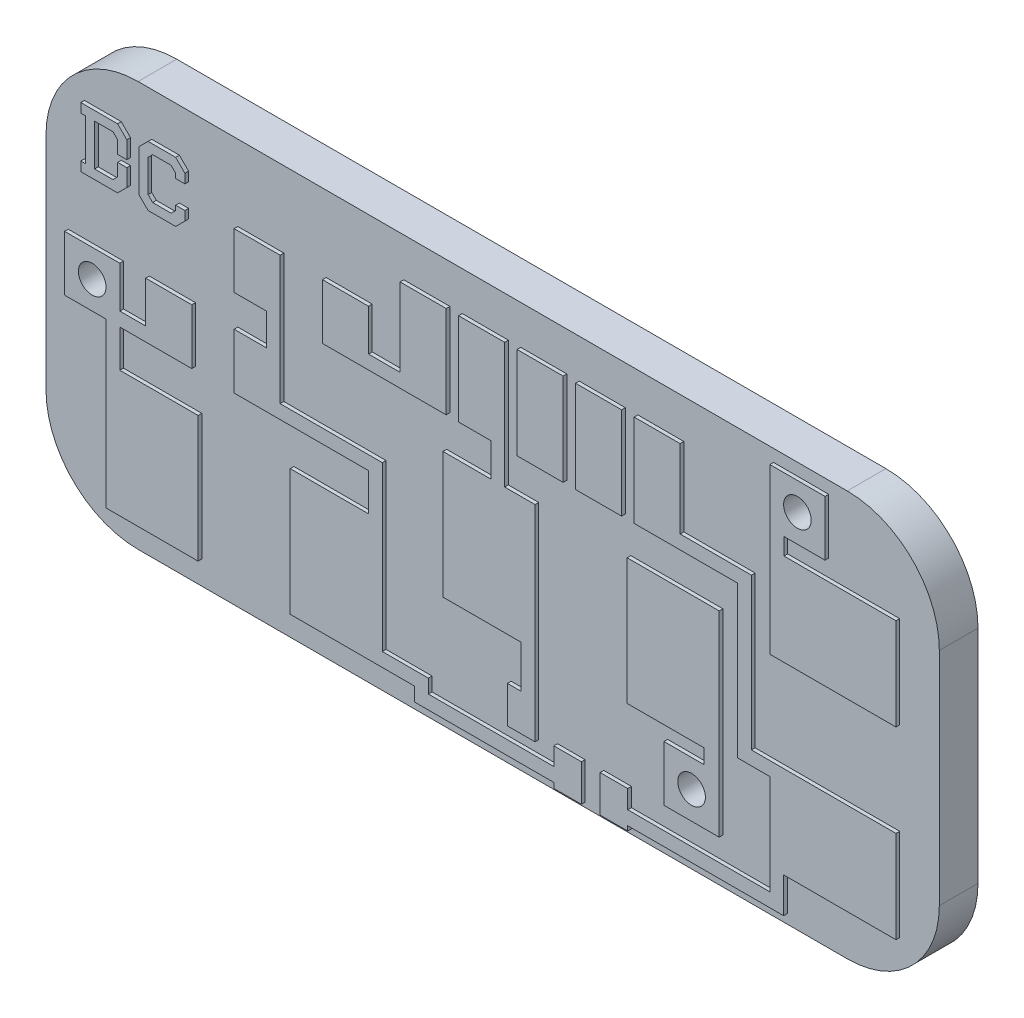
SolidWorks part; units mm, degrees
ref_plane "Front Plane" through (0, 0, 0) normal (0, 0, 1) x (1, 0, 0)
ref_plane "Top Plane" through (0, 0, 0) normal (0, 1, 0) x (1, 0, 0)
ref_plane "Right Plane" through (0, 0, 0) normal (1, 0, 0) x (0, 0, -1)
sketch "Sketch1" plane through (0, 0, 0) normal (0, 0, 1) x (1, 0, 0)
  line L0 (0, 4.4) -> (0, 0)
  line L1 (0, 0) -> (9.7, 0)
  line L2 (9.7, 0) -> (9.7, 4.4)
  line L3 (9.7, 4.4) -> (0, 4.4)
extrude "Boss-Extrude1" add sketch "Sketch1" against normal blind 0.42
fillet "Fillet1" radius 1 1 edges at (0, 0, -0.21)
fillet "Fillet2" radius 1 1 edges at (0, 4.4, -0.21)
fillet "Fillet3" radius 1 1 edges at (9.7, 0, -0.21)
fillet "Fillet4" radius 1 1 edges at (9.7, 4.4, -0.21)
sketch "Sketch2" plane through (0, 0, 0) normal (0, 0, 1) x (1, 0, 0)
  line L0 (3.6916, 0.4057) -> (4.1916, 0.4057)
  line L1 (4.1916, 0.4057) -> (4.1916, 0.2557)
  line L2 (4.1916, 0.2557) -> (5.5535, 0.2557)
  line L3 (5.5535, 0.2557) -> (5.5535, 0.45)
  line L4 (5.5535, 0.45) -> (5.8535, 0.45)
  line L5 (5.8535, 0.45) -> (5.8535, 0.05)
  line L6 (5.8535, 0.05) -> (5.5535, 0.05)
  line L7 (5.5535, 0.05) -> (5.5535, 0.1057)
  line L8 (5.5535, 0.1057) -> (4.0416, 0.1057)
  line L9 (4.0416, 0.1057) -> (4.0416, 0.2557)
  line L10 (4.0416, 0.2557) -> (2.6916, 0.2557)
  line L11 (2.6916, 0.2557) -> (2.6916, 1.6257)
  line L12 (2.6916, 1.6257) -> (3.5416, 1.6257)
  line L13 (3.5416, 1.6257) -> (3.5416, 2.0319)
  line L14 (3.5416, 2.0319) -> (2.0824, 2.0319)
  line L15 (2.0824, 2.0319) -> (2.0824, 2.6319)
  line L16 (2.0824, 2.6319) -> (2.4324, 2.6319)
  line L17 (2.4324, 2.6319) -> (2.4324, 2.9779)
  line L18 (2.4324, 2.9779) -> (2.0824, 2.9779)
  line L19 (2.0824, 2.9779) -> (2.0824, 3.5779)
  line L20 (2.0824, 3.5779) -> (2.5824, 3.5779)
  line L21 (2.5824, 3.5779) -> (2.5824, 2.1819)
  line L22 (2.5824, 2.1819) -> (3.6916, 2.1819)
  line L23 (3.6916, 2.1819) -> (3.6916, 0.4057)
extrude "Boss-Extrude2" add sketch "Sketch2" along normal blind 0.04
sketch "Sketch3" plane through (0, 0, 0) normal (0, 0, 1) x (1, 0, 0)
  line L0 (6.3567, 0.05) -> (6.0567, 0.05)
  line L1 (6.0567, 0.05) -> (6.0567, 0.45)
  line L2 (6.0567, 0.45) -> (6.3567, 0.45)
  line L3 (6.3567, 0.45) -> (6.3567, 0.25)
  line L4 (6.3567, 0.25) -> (7.8993, 0.25)
  line L5 (7.8993, 0.25) -> (7.8993, 1.3342)
  line L6 (7.8993, 1.3342) -> (7.5493, 1.3342)
  line L7 (7.5493, 1.3342) -> (7.5493, 2.9779)
  line L8 (7.5493, 2.9779) -> (6.4257, 2.9779)
  line L9 (6.4257, 2.9779) -> (6.4257, 3.9779)
  line L10 (6.4257, 3.9779) -> (6.9257, 3.9779)
  line L11 (6.9257, 3.9779) -> (6.9257, 3.1279)
  line L12 (6.9257, 3.1279) -> (7.6993, 3.1279)
  line L13 (7.6993, 3.1279) -> (7.6993, 1.4842)
  line L14 (7.6993, 1.4842) -> (9.2693, 1.4842)
  line L15 (9.2693, 1.4842) -> (9.2693, 0.4842)
  line L16 (9.2693, 0.4842) -> (8.0493, 0.4842)
  line L17 (8.0493, 0.4842) -> (8.0493, 0.1)
  line L18 (8.0493, 0.1) -> (6.3567, 0.1)
  line L19 (6.3567, 0.1) -> (6.3567, 0.05)
extrude "Boss-Extrude3" add sketch "Sketch3" along normal blind 0.04
sketch "Sketch4" plane through (0, 0, 0) normal (0, 0, 1) x (1, 0, 0)
  line L0 (1.1483, 3.8311) -> (1.1483, 3.3811)
  line L1 (1.1483, 3.3811) -> (1.3983, 3.3811)
  line L2 (1.3983, 3.3811) -> (1.4483, 3.4311)
  line L3 (1.4483, 3.4311) -> (1.4483, 3.4811)
  line L4 (1.4483, 3.4811) -> (1.5483, 3.4811)
  line L5 (1.5483, 3.4811) -> (1.5483, 3.3811)
  line L6 (1.5483, 3.3811) -> (1.4483, 3.2811)
  line L7 (1.4483, 3.2811) -> (1.0483, 3.2811)
  line L8 (1.0483, 3.2811) -> (1.0483, 3.9311)
  line L9 (1.0483, 3.9311) -> (1.4483, 3.9311)
  line L10 (1.4483, 3.9311) -> (1.5483, 3.8311)
  line L11 (1.5483, 3.8311) -> (1.5483, 3.7311)
  line L12 (1.5483, 3.7311) -> (1.4483, 3.7311)
  line L13 (1.4483, 3.7311) -> (1.4483, 3.7811)
  line L14 (1.4483, 3.7811) -> (1.3983, 3.8311)
  line L15 (1.3983, 3.8311) -> (1.1483, 3.8311)
extrude "Boss-Extrude4" add sketch "Sketch4" along normal blind 0.04
sketch "Sketch5" plane through (0, 0, 0) normal (0, 0, 1) x (1, 0, 0)
  line L0 (0.4175, 3.2811) -> (0.4175, 3.3811)
  line L1 (0.4175, 3.3811) -> (0.4675, 3.3811)
  line L2 (0.4675, 3.3811) -> (0.4675, 3.8311)
  line L3 (0.4675, 3.8311) -> (0.4175, 3.8311)
  line L4 (0.4175, 3.8311) -> (0.4175, 3.9311)
  line L5 (0.4175, 3.9311) -> (0.9175, 3.9311)
  line L6 (0.9175, 3.9311) -> (0.9175, 3.6436)
  line L7 (0.9175, 3.6436) -> (0.8175, 3.6436)
  line L8 (0.8175, 3.6436) -> (0.8175, 3.8311)
  line L9 (0.8175, 3.8311) -> (0.5675, 3.8311)
  line L10 (0.5675, 3.8311) -> (0.5675, 3.3811)
  line L11 (0.5675, 3.3811) -> (0.8175, 3.3811)
  line L12 (0.8175, 3.3811) -> (0.8175, 3.5686)
  line L13 (0.8175, 3.5686) -> (0.9175, 3.5686)
  line L14 (0.9175, 3.5686) -> (0.9175, 3.2811)
  line L15 (0.9175, 3.2811) -> (0.4175, 3.2811)
extrude "Boss-Extrude5" add sketch "Sketch5" along normal blind 0.04
sketch "Sketch6" plane through (0, 0, 0) normal (0, 0, 1) x (1, 0, 0)
  line L0 (5.35, 0.3854) -> (5.05, 0.3854)
  line L1 (5.05, 0.3854) -> (5.05, 0.7854)
  line L2 (5.05, 0.7854) -> (5.2, 0.7854)
  line L3 (5.2, 0.7854) -> (5.2, 1.2467)
  line L4 (5.2, 1.2467) -> (4.35, 1.2467)
  line L5 (4.35, 1.2467) -> (4.35, 2.6167)
  line L6 (4.35, 2.6167) -> (4.8698, 2.6167)
  line L7 (4.8698, 2.6167) -> (4.8698, 2.9779)
  line L8 (4.8698, 2.9779) -> (4.5198, 2.9779)
  line L9 (4.5198, 2.9779) -> (4.5198, 3.9779)
  line L10 (4.5198, 3.9779) -> (5.0198, 3.9779)
  line L11 (5.0198, 3.9779) -> (5.0198, 2.6167)
  line L12 (5.0198, 2.6167) -> (5.35, 2.6167)
  line L13 (5.35, 2.6167) -> (5.35, 0.3854)
extrude "Boss-Extrude6" add sketch "Sketch6" along normal blind 0.04
sketch "Sketch7" plane through (0, 0, 0) normal (0, 0, 1) x (1, 0, 0)
  line L0 (1.6916, 1.6257) -> (1.6916, 0.2557)
  line L1 (1.6916, 0.2557) -> (0.6916, 0.2557)
  line L2 (0.6916, 0.2557) -> (0.6916, 2.0319)
  line L3 (0.6916, 2.0319) -> (0.2416, 2.0319)
  line L4 (0.2416, 2.0319) -> (0.2416, 2.6319)
  line L5 (0.2416, 2.6319) -> (0.8416, 2.6319)
  line L6 (0.8416, 2.6319) -> (0.8416, 2.1819)
  line L7 (0.8416, 2.1819) -> (1.1229, 2.1819)
  line L8 (1.1229, 2.1819) -> (1.1229, 2.6319)
  line L9 (1.1229, 2.6319) -> (1.6229, 2.6319)
  line L10 (1.6229, 2.6319) -> (1.6229, 2.0319)
  line L11 (1.6229, 2.0319) -> (0.8416, 2.0319)
  line L12 (0.8416, 2.0319) -> (0.8416, 1.6257)
  line L13 (0.8416, 1.6257) -> (1.6916, 1.6257)
extrude "Boss-Extrude7" add sketch "Sketch7" along normal blind 0.04
sketch "Sketch8" plane through (0, 0, 0) normal (0, 0, 1) x (1, 0, 0)
  line L0 (3.542, 3.5779) -> (3.542, 3.1279)
  line L1 (3.542, 3.1279) -> (3.8848, 3.1279)
  line L2 (3.8848, 3.1279) -> (3.8848, 3.9779)
  line L3 (3.8848, 3.9779) -> (4.3848, 3.9779)
  line L4 (4.3848, 3.9779) -> (4.3848, 2.9779)
  line L5 (4.3848, 2.9779) -> (3.0419, 2.9779)
  line L6 (3.0419, 2.9779) -> (3.0419, 3.5779)
  line L7 (3.0419, 3.5779) -> (3.542, 3.5779)
extrude "Boss-Extrude8" add sketch "Sketch8" along normal blind 0.04
sketch "Sketch9" plane through (0, 0, 0) normal (0, 0, 1) x (1, 0, 0)
  line L0 (6.75, 1.0887) -> (7.1837, 1.0887)
  line L1 (7.1837, 1.0887) -> (7.1837, 1.2467)
  line L2 (7.1837, 1.2467) -> (6.35, 1.2467)
  line L3 (6.35, 1.2467) -> (6.35, 2.6167)
  line L4 (6.35, 2.6167) -> (7.35, 2.6167)
  line L5 (7.35, 2.6167) -> (7.35, 0.4887)
  line L6 (7.35, 0.4887) -> (6.75, 0.4887)
  line L7 (6.75, 0.4887) -> (6.75, 1.0887)
extrude "Boss-Extrude9" add sketch "Sketch9" along normal blind 0.04
sketch "Sketch10" plane through (0, 0, 0) normal (0, 0, 1) x (1, 0, 0)
  line L0 (8.4993, 3.668) -> (8.0533, 3.668)
  line L1 (8.0533, 3.668) -> (8.0533, 3.4842)
  line L2 (8.0533, 3.4842) -> (9.2693, 3.4842)
  line L3 (9.2693, 3.4842) -> (9.2693, 2.4842)
  line L4 (9.2693, 2.4842) -> (7.8993, 2.4842)
  line L5 (7.8993, 2.4842) -> (7.8993, 4.268)
  line L6 (7.8993, 4.268) -> (8.4993, 4.268)
  line L7 (8.4993, 4.268) -> (8.4993, 3.668)
extrude "Boss-Extrude10" add sketch "Sketch10" along normal blind 0.04
sketch "Sketch11" plane through (0, 0, 0) normal (0, 0, 1) x (1, 0, 0)
  line L0 (5.6548, 2.9779) -> (5.1548, 2.9779)
  line L1 (5.1548, 2.9779) -> (5.1548, 3.9779)
  line L2 (5.1548, 3.9779) -> (5.6548, 3.9779)
  line L3 (5.6548, 3.9779) -> (5.6548, 2.9779)
extrude "Boss-Extrude11" add sketch "Sketch11" along normal blind 0.04
sketch "Sketch12" plane through (0, 0, 0) normal (0, 0, 1) x (1, 0, 0)
  line L0 (6.2907, 2.9779) -> (5.7907, 2.9779)
  line L1 (5.7907, 2.9779) -> (5.7907, 3.9779)
  line L2 (5.7907, 3.9779) -> (6.2907, 3.9779)
  line L3 (6.2907, 3.9779) -> (6.2907, 2.9779)
extrude "Boss-Extrude12" add sketch "Sketch12" along normal blind 0.04
sketch "Sketch19" plane through (0, 0, -0.42) normal (0, 0, -1) x (-1, 0, 0)
  line L8 (-1, 4.3) -> (-8.7, 4.3)
  line L9 (-9.6, 3.4) -> (-9.6, 1)
  line L10 (-8.7, 0.1) -> (-1, 0.1)
  line L11 (-0.1, 1) -> (-0.1, 3.4)
  line L12 (-1, 4.3) -> (-8.7, 4.3)
  line L13 (-9.6, 3.4) -> (-9.6, 1)
  line L14 (-8.7, 0.1) -> (-1, 0.1)
  line L15 (-0.1, 1) -> (-0.1, 3.4)
  arc A8 (-8.7, 4.3) -> (-9.6, 3.4) centre (-8.7, 3.4) ccw
  arc A9 (-9.6, 1) -> (-8.7, 0.1) centre (-8.7, 1) ccw
  arc A10 (-1, 0.1) -> (-0.1, 1) centre (-1, 1) ccw
  arc A11 (-0.1, 3.4) -> (-1, 4.3) centre (-1, 3.4) ccw
  arc A12 (-8.7, 4.3) -> (-9.6, 3.4) centre (-8.7, 3.4) ccw
  arc A13 (-9.6, 1) -> (-8.7, 0.1) centre (-8.7, 1) ccw
  arc A14 (-1, 0.1) -> (-0.1, 1) centre (-1, 1) ccw
  arc A15 (-0.1, 3.4) -> (-1, 4.3) centre (-1, 3.4) ccw
  dimension "D1" = 0.1
extrude "Boss-Extrude13" add sketch "Sketch19" along normal blind 0.025
hole_wizard "Hole1" positions "Sketch14" profile "Sketch13" legacy
sketch "Sketch14" plane through (0, 0, 0.04) normal (0, 0, 1) x (1, 0, 0)
  point P0 (8.1993, 3.968)
sketch "Sketch13" plane through (8.1993, 3.968, 0.04) normal (1, 0, 0) x (0, -1, 0)
  line L0 (0, 0) -> (0, 0.485)
  line L1 (0, 0.485) -> (0.15, 0.485)
  line L2 (0.15, 0.485) -> (0.15, 0)
  line L3 (0.15, 0) -> (0, 0)
  line L4 (0, 110) -> (0, -10) construction
  dimension "Diameter" = 0.3
  dimension "Depth" = 0.485
hole_wizard "Hole2" positions "Sketch16" profile "Sketch15" legacy
sketch "Sketch16" plane through (0, 0, 0.04) normal (0, 0, 1) x (1, 0, 0)
  point P0 (7.05, 0.7887)
sketch "Sketch15" plane through (7.05, 0.7887, 0.04) normal (1, 0, 0) x (0, -1, 0)
  line L0 (0, 0) -> (0, 0.485)
  line L1 (0, 0.485) -> (0.15, 0.485)
  line L2 (0.15, 0.485) -> (0.15, 0)
  line L3 (0.15, 0) -> (0, 0)
  line L4 (0, 110) -> (0, -10) construction
  dimension "Diameter" = 0.3
  dimension "Depth" = 0.485
hole_wizard "Hole3" positions "Sketch18" profile "Sketch17" legacy
sketch "Sketch18" plane through (0, 0, 0.04) normal (0, 0, 1) x (1, 0, 0)
  point P0 (0.5416, 2.3319)
sketch "Sketch17" plane through (0.5416, 2.3319, 0.04) normal (1, 0, 0) x (0, -1, 0)
  line L0 (0, 0) -> (0, 0.485)
  line L1 (0, 0.485) -> (0.15, 0.485)
  line L2 (0.15, 0.485) -> (0.15, 0)
  line L3 (0.15, 0) -> (0, 0)
  line L4 (0, 110) -> (0, -10) construction
  dimension "Diameter" = 0.3
  dimension "Depth" = 0.485
chamfer "Chamfer1" distance 0.1 angle 45 1 edges at (0.9175, 3.9311, 0.02)
chamfer "Chamfer2" distance 0.05 angle 45 1 edges at (1.1483, 3.8311, 0.02)
chamfer "Chamfer3" distance 0.1 angle 45 1 edges at (0.9175, 3.2811, 0.02)
chamfer "Chamfer4" distance 0.05 angle 45 1 edges at (0.8175, 3.8311, 0.02)
chamfer "Chamfer5" distance 0.1 angle 45 1 edges at (1.0483, 3.2811, 0.02)
chamfer "Chamfer6" distance 0.1 angle 45 1 edges at (1.0483, 3.9311, 0.02)
chamfer "Chamfer7" distance 0.05 angle 45 1 edges at (1.1483, 3.3811, 0.02)
chamfer "Chamfer8" distance 0.05 angle 45 1 edges at (0.8175, 3.3811, 0.02)
